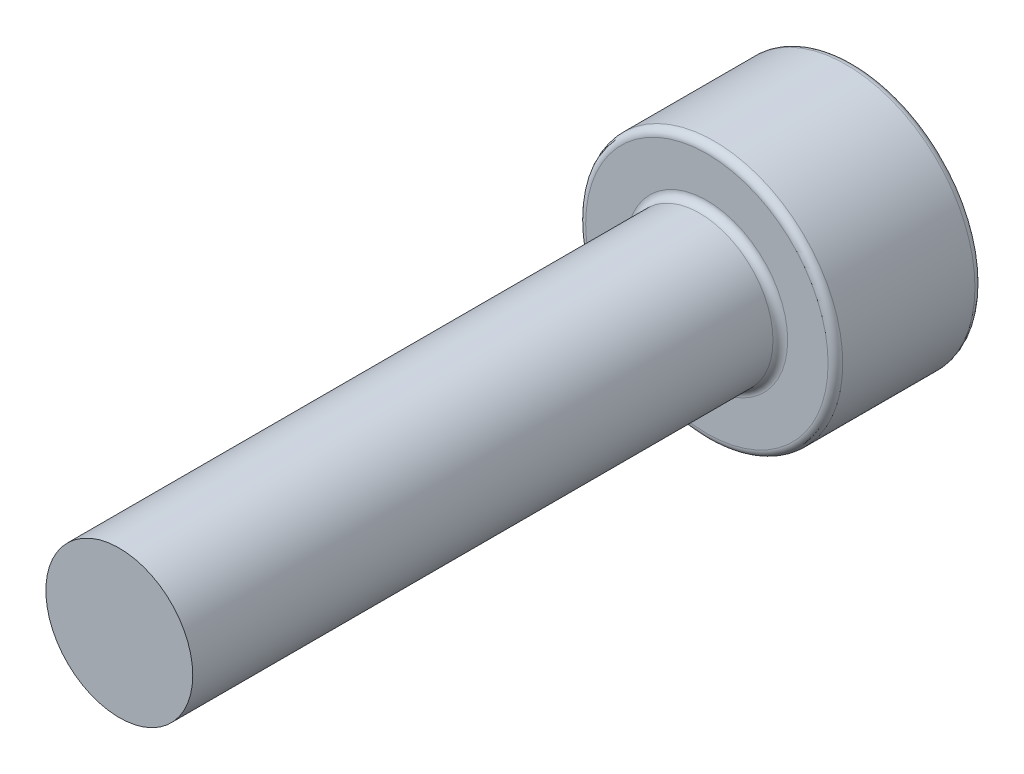
SolidWorks part; units mm, degrees
ref_plane "Plan de face" through (0, 0, 0) normal (0, 0, 1) x (1, 0, 0)
ref_plane "Plan de dessus" through (0, 0, 0) normal (0, 1, 0) x (1, 0, 0)
ref_plane "Plan de droite" through (0, 0, 0) normal (1, 0, 0) x (0, 0, -1)
sketch "Esquisse1" plane through (0, 0, 0) normal (0, 0, 1) x (1, 0, 0)
  line L1 (0.5774, -1) -> (1.1547, 0)
  line L2 (1.1547, 0) -> (0.5774, 1)
  line L3 (0.5774, 1) -> (-0.5774, 1)
  line L4 (-0.5774, 1) -> (-1.1547, 0)
  line L5 (-1.1547, 0) -> (-0.5774, -1)
  line L6 (-0.5774, -1) -> (0.5774, -1)
  circle A0 centre (0, 0) radius 1.75
  circle A1 centre (0, 0) radius 1 construction
  dimension "D1" = 3.5
  dimension "D2" = 2
extrude "Boss.-Extru.1" add sketch "Esquisse1" along normal blind 2
sketch "Esquisse2" plane through (0, 0, 2) normal (0, 0, 1) x (1, 0, 0)
  circle A0 centre (0, 0) radius 1
  dimension "D1" = 2
sketch "Esquisse3" plane through (0, 0, 2) normal (0, 0, 1) x (1, 0, 0)
  circle A0 centre (0, 0) radius 1.75
  circle A1 centre (0, 0) radius 1.75 construction
extrude "Boss.-Extru.2" add sketch "Esquisse3" against normal blind 0.25
extrude "Boss.-Extru.3" add sketch "Esquisse2" along normal blind 8
fillet "Congé1" radius 0.1 3 edges at (1.75, 0, 2) (1.75, 0, 0) (1, 0, 2)
